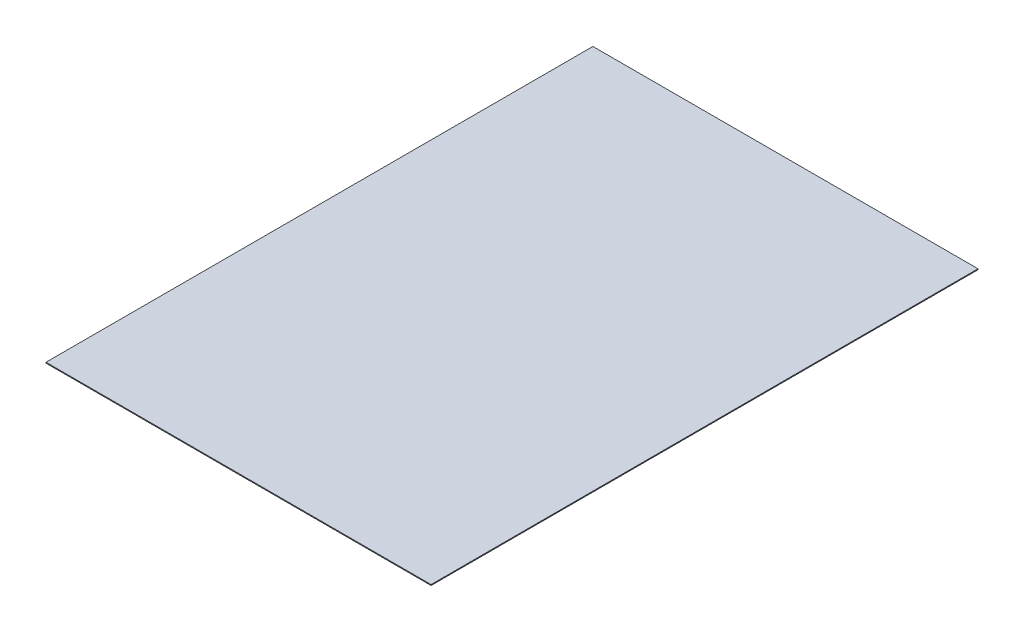
SolidWorks part; units mm, degrees
material "6061-T6 (SS)"
ref_plane "Front Plane" through (0, 0, 0) normal (0, 0, 1) x (1, 0, 0)
ref_plane "Top Plane" through (0, 0, 0) normal (0, 1, 0) x (1, 0, 0)
ref_plane "Right Plane" through (0, 0, 0) normal (1, 0, 0) x (0, 0, -1)
sketch "Sketch1" plane through (0, 0, 0) normal (0, 1, 0) x (1, 0, 0)
  line L1 (0, 0) -> (2000, 0)
  line L2 (0, 0) -> (0, -2000)
  line L3 (0, -2000) -> (2000, -2000)
  line L4 (2000, 0) -> (2000, -2000)
  dimension "D1" = 2000
  dimension "D2" = 2000
extrude "Boss-Extrude1" add sketch "Sketch1" along normal blind 3.175
sketch "Sketch3" plane through (0, 0, 0) normal (0, -1, 0) x (1, 0, 0)
  line L0 (0, 2000) -> (2000, 0) construction
  line L1 (0, 0) -> (2000, 2000) construction
  line L3 (2000, 0) -> (0, 0) construction
  line L5 (2000, 2000) -> (2000, 0) construction
  line L7 (0, 0) -> (0, 2000) construction
  line L9 (0, 2000) -> (2000, 2000) construction
  line L10 (1000, 500) -> (1000, 0) construction
  line L11 (1500, 1000) -> (2000, 1000)
  line L12 (500, 1000) -> (0, 1000)
  line L13 (1000, 1500) -> (1000, 2000)
  point P8 (1000, 1000)
  point P9 (1000, 250)
  point P13 (1000, 500)
  point P23 (1500, 1000)
  point P24 (500, 1000)
  point P25 (1000, 1500)
  point P30 (250, 1000)
  point P31 (1000, 1750)
  point P32 (1750, 1000)
sketch "Sketch4" plane through (0, 3.175, 0) normal (0, 1, 0) x (1, 0, 0)
  line L0 (0, -2000) -> (2000, -2000) construction
  line L1 (0, 0) -> (591.8242, 0)
  line L2 (0, 0) -> (0, -2000)
  line L3 (0, -2000) -> (591.8242, -2000)
  line L4 (591.8242, 0) -> (591.8242, -2000)
extrude "Cut-Extrude1" cut sketch "Sketch4" against normal through all
